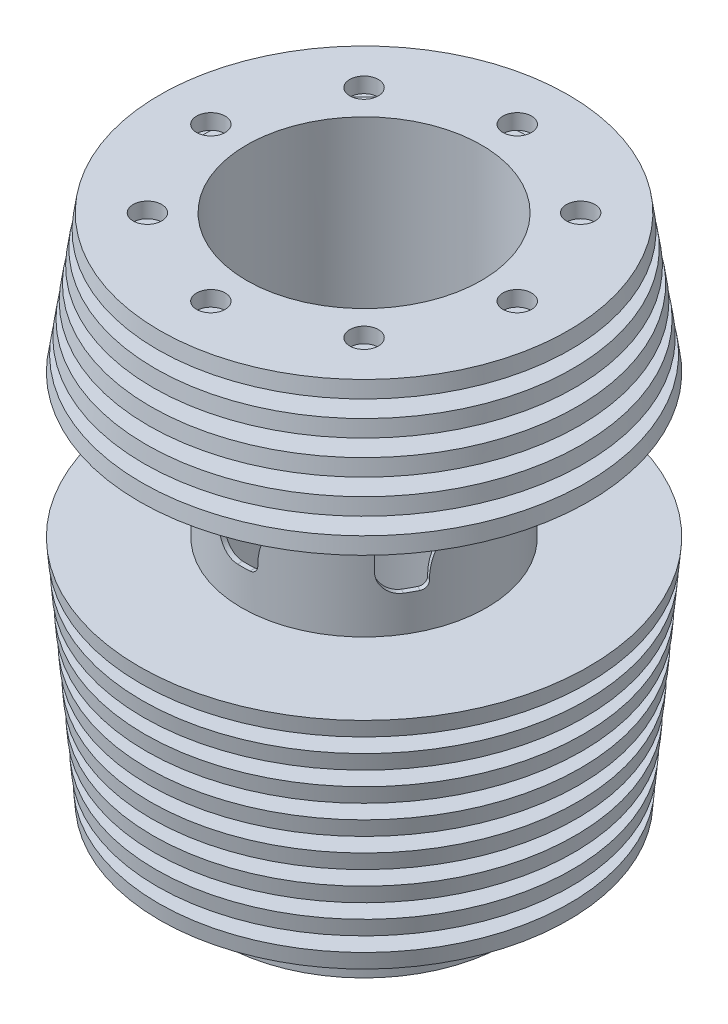
SolidWorks part; units mm, degrees
ref_plane "Front Plane" through (0, 0, 0) normal (0, 0, 1) x (1, 0, 0)
ref_plane "Top Plane" through (0, 0, 0) normal (0, 1, 0) x (1, 0, 0)
ref_plane "Right Plane" through (0, 0, 0) normal (1, 0, 0) x (0, 0, -1)
sketch "Sketch1" plane through (0, 0, 0) normal (0, 0, 1) x (1, 0, 0)
  line L0 (0, 0) -> (-20, 0)
  line L1 (-20, 0) -> (-22.2222, -15) construction
  line L2 (-20.2222, -1.5) -> (-16, -1.5)
  line L3 (-16, -1.5) -> (-16, -3)
  line L4 (-16, -3) -> (-20.4444, -3)
  line L5 (-20.4444, -3) -> (-20.6667, -4.5)
  line L6 (-20.6667, -4.5) -> (-13, -4.5)
  line L7 (-13, -4.5) -> (-13, -6)
  line L8 (-13, -6) -> (-20.8889, -6)
  line L9 (-20.8889, -6) -> (-21.1111, -7.5)
  line L10 (-21.1111, -7.5) -> (-13, -7.5)
  line L11 (-13, -7.5) -> (-13, -9)
  line L12 (-13, -9) -> (-21.3333, -9)
  line L13 (-21.3333, -9) -> (-21.5556, -10.5)
  line L14 (-21.5556, -10.5) -> (-13, -10.5)
  line L15 (-13, -10.5) -> (-13, -12)
  line L16 (-13, -12) -> (-21.7778, -12)
  line L17 (-21.7778, -12) -> (-22, -13.5)
  line L18 (-22, -13.5) -> (-12, -13.5)
  line L19 (-12, -13.5) -> (-12, -27.5)
  line L20 (-12, -27.5) -> (-22, -27.5)
  line L21 (-20, 0) -> (-20, -50) construction
  line L22 (-22, -27.5) -> (-20, -50) construction
  line L23 (-22, -27.5) -> (-21.8667, -29)
  line L24 (-21.8667, -29) -> (-13, -29)
  line L25 (-13, -29) -> (-13, -30.5)
  line L26 (-13, -30.5) -> (-21.7333, -30.5)
  line L27 (-21.7333, -30.5) -> (-21.6, -32)
  line L28 (-21.6, -32) -> (-13, -32)
  line L29 (-13, -32) -> (-13, -33.5)
  line L30 (-13, -33.5) -> (-21.4667, -33.5)
  line L31 (-21.4667, -33.5) -> (-21.3333, -35)
  line L32 (-21.3333, -35) -> (-13, -35)
  line L33 (-13, -35) -> (-13, -36.5)
  line L34 (-13, -36.5) -> (-21.2, -36.5)
  line L35 (-21.2, -36.5) -> (-21.0667, -38)
  line L36 (-21.0667, -38) -> (-13, -38)
  line L37 (-13, -38) -> (-13, -39.5)
  line L38 (-13, -39.5) -> (-20.9333, -39.5)
  line L39 (-20.9333, -39.5) -> (-20.8, -41)
  line L40 (-20.8, -41) -> (-13, -41)
  line L41 (-13, -41) -> (-13, -42.5)
  line L42 (-13, -42.5) -> (-20.6667, -42.5)
  line L43 (-20.6667, -42.5) -> (-20.5333, -44)
  line L44 (-20.5333, -44) -> (-13, -44)
  line L45 (-13, -44) -> (-13, -45.5)
  line L46 (-13, -45.5) -> (-20.4, -45.5)
  line L47 (-20.4, -45.5) -> (-20.2667, -47)
  line L48 (-20.2667, -47) -> (-13, -47)
  line L49 (-13, -47) -> (-13, -48.5)
  line L50 (-13, -48.5) -> (-20.1333, -48.5)
  line L51 (-20.1333, -48.5) -> (-20, -50)
  line L52 (-20, -50) -> (-14, -50)
  line L54 (0, -50) -> (0, 0)
  line L55 (-20.2222, -1.5) -> (-20, 0)
  line L56 (-14, -50) -> (-14, -55)
  line L57 (-14, -55) -> (0, -55)
  line L58 (0, -55) -> (0, -50)
  line L59 (0, 9.0361) -> (0, 0) construction
  point P45 (-13, -44.75)
  dimension "D1" = 1.5
  dimension "D2" = 1.5
  dimension "D3" = 1.5
  dimension "D4" = 1.5
  dimension "D5" = 1.5
  dimension "D6" = 1.5
  dimension "D7" = 1.5
  dimension "D8" = 1.5
  dimension "D9" = 1.5
  dimension "D10" = 1.5
  dimension "D11" = 1.5
  dimension "D12" = 1.5
  dimension "D13" = 1.5
  dimension "D14" = 1.5
  dimension "D15" = 20
  dimension "D16" = 14
  dimension "D17" = 22
  dimension "D18" = 12
  dimension "D19" = 13
  dimension "D20" = 16
  dimension "D21" = 5
  dimension "D22" = 14
revolve "Revolve1" add sketch "Sketch1" angle 360 about L59
sketch "Sketch2" plane through (0, 0, 0) normal (0, 1, 0) x (1, 0, 0)
  circle A1 centre (0, 0) radius 11.5
  dimension "D1" = 23
extrude "Cut-Extrude1" cut sketch "Sketch2" against normal through all
sketch "Sketch3" plane through (0, 0, 0) normal (0, 1, 0) x (1, 0, 0)
  circle A0 centre (0, 15) radius 1.4
  circle A1 centre (0, 0) radius 15 construction
  circle A2 centre (10.6066, 10.6066) radius 1.4
  circle A3 centre (15, 0) radius 1.4
  circle A4 centre (10.6066, -10.6066) radius 1.4
  circle A5 centre (0, -15) radius 1.4
  circle A6 centre (-10.6066, -10.6066) radius 1.4
  circle A7 centre (-15, 0) radius 1.4
  circle A8 centre (-10.6066, 10.6066) radius 1.4
  point P6 (0, 0)
  point P21 (0, 0)
  dimension "D1" = 2.8
  dimension "D2" = 30
  dimension "D3" = 8
extrude "Cut-Extrude2" cut sketch "Sketch3" against normal blind 1.5
sketch "Sketch4" plane through (0, 0, 0) normal (0, 0, 1) x (1, 0, 0)
  line L0 (2.4, -17) -> (-2.4, -17)
  line L1 (2.4, -17) -> (2.4, -22)
  line L2 (0.4, -24) -> (-0.7989, -24)
  arc A0 (-2.4, -17) -> (-3.2343, -19.0625) centre (-2.4, -18.2) ccw
  arc A1 (-3.2343, -19.0625) -> (-1.4987, -23.2846) centre (-7.1973, -23.1594) cw
  arc A2 (-1.4987, -23.2846) -> (-0.7989, -24) centre (-0.7989, -23.3) ccw
  arc A3 (2.4, -22) -> (0.4, -24) centre (0.4, -22) cw
  point P3 (0, -17)
  point P11 (0, 0)
  point P12 (0, 0)
  point P16 (2.4, -24)
  dimension "D1" = 2.4
  dimension "D4" = 2
  dimension "D5" = 5.7
  dimension "D6" = 0.7
  dimension "D2" = 4.8
  dimension "D3" = 7
  dimension "D7" = 24
extrude "Cut-Extrude4" cut sketch "Sketch4" against normal through all
pattern_circular "CirPattern1" count 6 over 360 about axis through (0, 0, 0) along (0, 1, 0) of "Cut-Extrude4"
